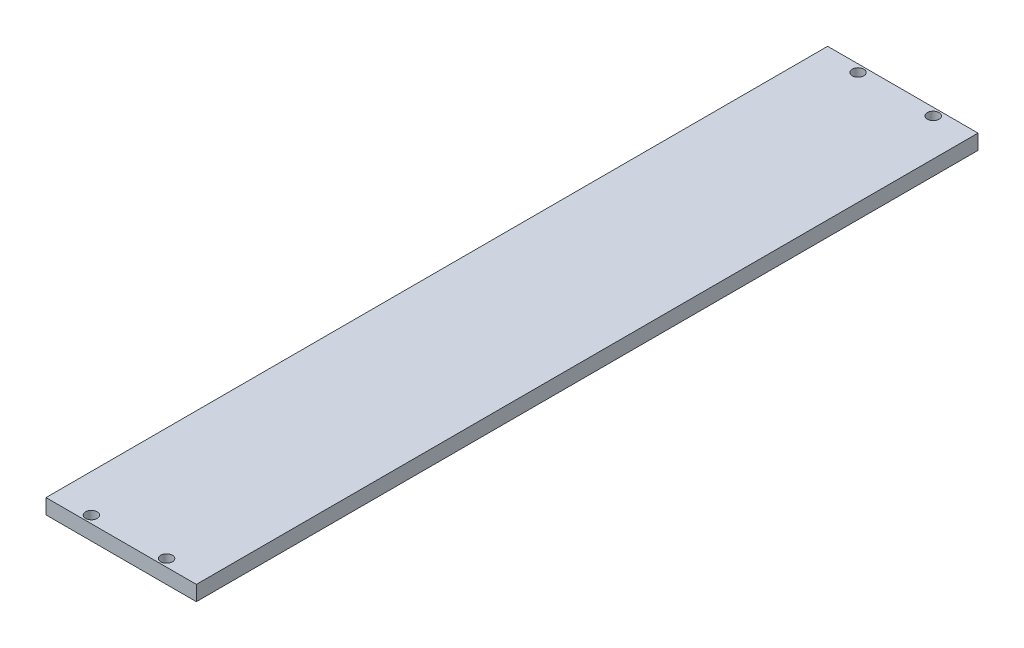
SolidWorks part; units mm, degrees
material "6061 Alloy"
ref_plane "Front Plane" through (0, 0, 0) normal (0, 0, 1) x (1, 0, 0)
ref_plane "Top Plane" through (0, 0, 0) normal (0, 1, 0) x (1, 0, 0)
ref_plane "Right Plane" through (0, 0, 0) normal (1, 0, 0) x (0, 0, -1)
sketch "Sketch1" plane through (0, 0, 0) normal (0, 1, 0) x (1, 0, 0)
  line L0 (-25.1507, 163.4825) -> (38.3493, 163.4825)
  line L1 (38.3493, 163.4825) -> (38.3493, -166.6675)
  line L2 (38.3493, -166.6675) -> (-25.1507, -166.6675)
  line L3 (-25.1507, -166.6675) -> (-25.1507, 163.4825)
  line L4 (-25.1507, 160.3075) -> (-9.2757, 160.3075) construction
  line L5 (-9.2757, 160.3075) -> (22.4743, 160.3075) construction
  line L6 (22.4743, 160.3075) -> (38.3493, 160.3075) construction
  line L7 (-25.1507, -163.4925) -> (-9.2757, -163.4925) construction
  line L8 (-9.2757, -163.4925) -> (22.4743, -163.4925) construction
  line L9 (22.4743, -163.4925) -> (38.3493, -163.4925) construction
  point P2 (-9.2757, 160.3075)
  point P5 (22.4743, 160.3075)
  point P6 (-9.2757, -163.4925)
  point P7 (22.4743, -163.4925)
extrude "Boss-Extrude1" add sketch "Sketch1" along normal blind 6.35
sketch "Sketch2" plane through (0, 6.35, 0) normal (0, 1, 0) x (1, 0, 0)
  line L10 (-25.1507, 163.4825) -> (-25.1507, 160.3075) construction
  line L11 (-25.1507, 163.4825) -> (-25.1507, -166.6675) construction
  line L12 (-25.1507, 160.3075) -> (-9.1487, 160.3075) construction
  line L13 (-9.1487, 160.3075) -> (22.6013, 160.3075) construction
  line L14 (22.6013, 160.3075) -> (38.3493, 160.3075) construction
  line L15 (38.3493, -166.6675) -> (38.3493, 163.4825) construction
  line L16 (38.3493, 160.3075) -> (38.3493, 163.4825) construction
  line L17 (-25.1507, -166.6675) -> (-25.1507, -163.4925) construction
  line L18 (-25.1507, -163.4925) -> (-9.1487, -163.4925) construction
  line L19 (-9.1487, -163.4925) -> (22.6013, -163.4925) construction
  line L20 (22.6013, -163.4925) -> (38.3493, -163.4925) construction
  line L21 (38.3493, -163.4925) -> (38.3493, -166.6675) construction
hole_wizard "#10 (0.1935) Diameter Hole1" positions "3DSketch1" profile "Sketch3" hole size "#10" standard "Ansi Inch"
sketch3d "3DSketch1"
  point P0 (22.6013, 6.35, -160.3075)
  point P4 (-9.1487, 6.35, -160.3075)
  point P7 (-9.1487, 6.35, 163.4925)
  point P10 (22.6013, 6.35, 163.4925)
sketch "Sketch3" plane through (22.6013, 6.35, -160.3075) normal (1, 0, 0) x (0, 0, 1)
  line L0 (0, 0) -> (0, 71.4766)
  line L1 (0, 71.4766) -> (2.4574, 70)
  line L2 (2.4574, 70) -> (2.4574, 0)
  line L5 (2.4574, 0) -> (0, 0)
  line L10 (0, 71.4766) -> (-2.4575, 70) construction
  line L11 (0, -6.35) -> (0, 107.95) construction
  dimension "Hole Dia." = 4.9149
  dimension "Hole Depth" = 70
  dimension "Drill Angle" = 118
